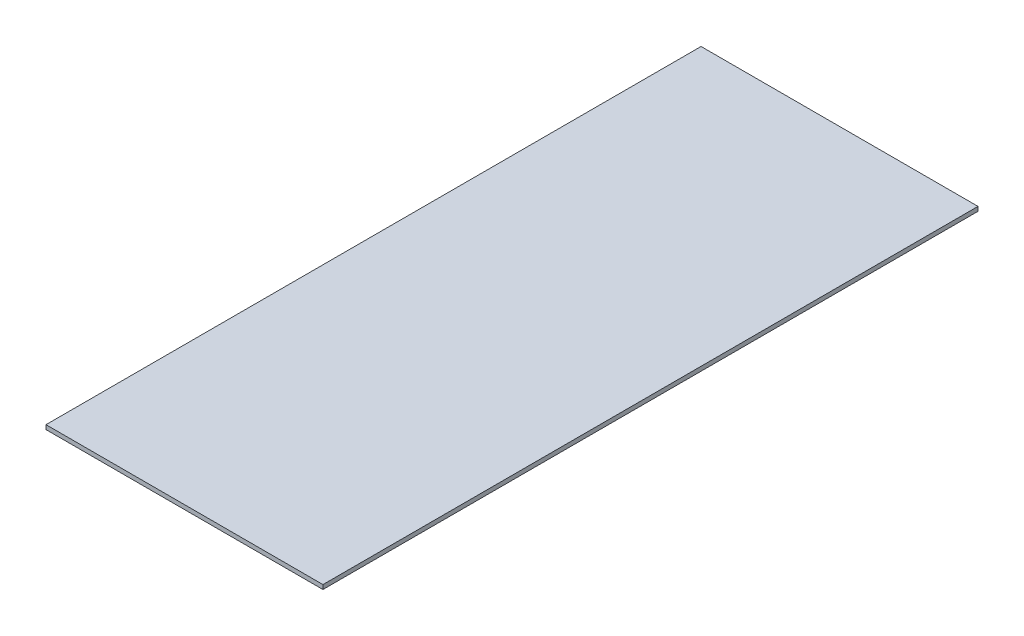
SolidWorks part; units mm, degrees
ref_plane "Front Plane" through (0, 0, 0) normal (0, 0, 1) x (1, 0, 0)
ref_plane "Top Plane" through (0, 0, 0) normal (0, 1, 0) x (1, 0, 0)
ref_plane "Right Plane" through (0, 0, 0) normal (1, 0, 0) x (0, 0, -1)
sketch "Sketch1" plane through (0, 0, 0) normal (0, 1, 0) x (1, 0, 0)
  line L1 (-96.65, 228.6) -> (96.65, 228.6)
  line L2 (-96.65, 228.6) -> (-96.65, -228.6)
  line L3 (-96.65, -228.6) -> (96.65, -228.6)
  line L4 (96.65, 228.6) -> (96.65, -228.6)
  line L5 (-96.65, 228.6) -> (96.65, -228.6) construction
  line L6 (-96.65, -228.6) -> (96.65, 228.6) construction
  point P0 (0, 0)
  dimension "D1" = 457.2
  dimension "D2" = 193.3
extrude "Boss-Extrude1" add sketch "Sketch1" along normal blind 3
